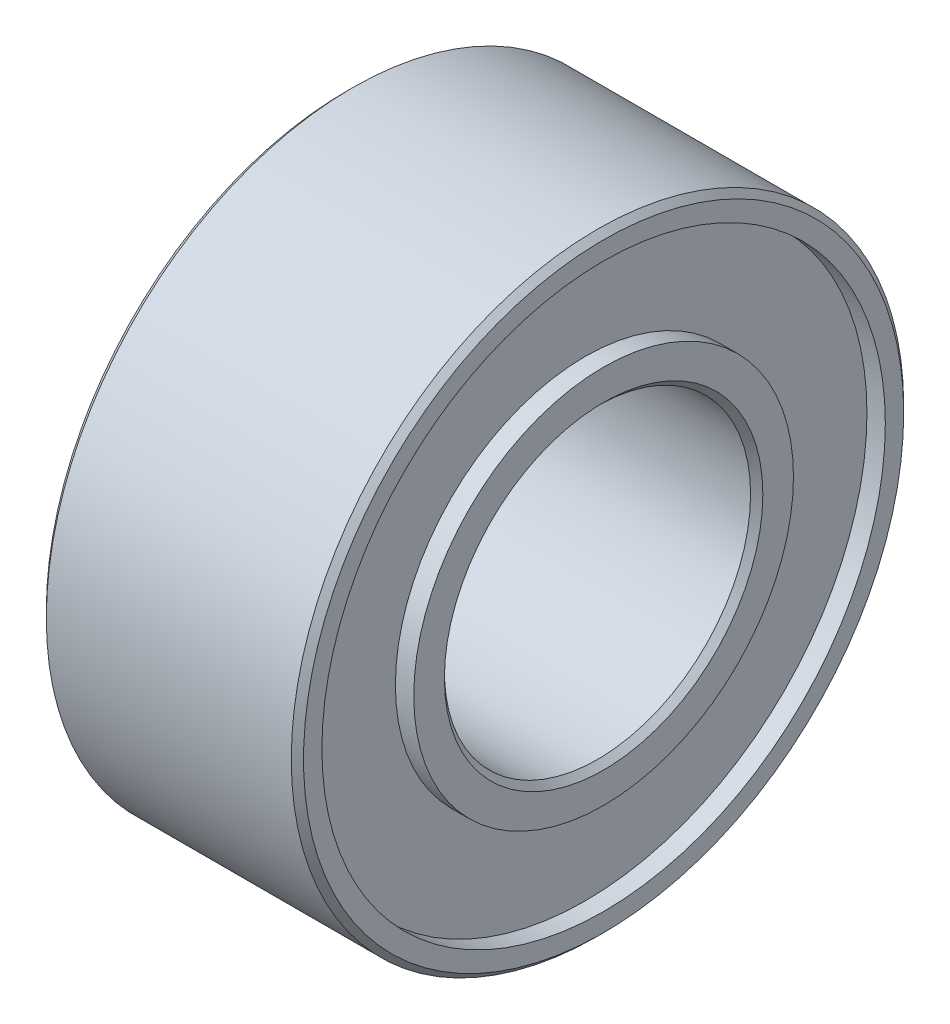
SolidWorks part; units mm, degrees
material "Plain Carbon Steel"
ref_plane "Front Plane" through (0, 0, 0) normal (0, 0, 1) x (1, 0, 0)
ref_plane "Top Plane" through (0, 0, 0) normal (0, 1, 0) x (1, 0, 0)
ref_plane "Right Plane" through (0, 0, 0) normal (1, 0, 0) x (0, 0, -1)
sketch "Sketch1" plane through (0, 0, 0) normal (0, 0, 1) x (1, 0, 0)
  line L0 (2.1, 2.5) -> (-2.1, 2.5)
  line L1 (-2.1, 2.5) -> (-2.1, 3.1)
  line L2 (-2.1, 3.1) -> (-1.8, 3.1)
  line L3 (-1.8, 3.1) -> (-1.8, 4.6)
  line L4 (-1.8, 4.6) -> (-2.1, 4.6)
  line L5 (-2.1, 4.6) -> (-2.1, 5)
  line L6 (-2.1, 5) -> (2.1, 5)
  line L7 (0, 5) -> (0, 2.5) construction
  line L8 (2.1, 4.6) -> (2.1, 5)
  line L9 (1.8, 4.6) -> (2.1, 4.6)
  line L10 (1.8, 3.1) -> (1.8, 4.6)
  line L11 (2.1, 3.1) -> (1.8, 3.1)
  line L12 (2.1, 2.5) -> (2.1, 3.1)
  line L13 (0, 0) -> (-4.3663, 0) construction
  dimension "D1" = 5
  dimension "D2" = 10
  dimension "D3" = 4.2
  dimension "D4" = 6.2
  dimension "D5" = 1.5
  dimension "D6" = 0.3
revolve "Revolve1" add sketch "Sketch1" angle 360 about L13
chamfer "Chamfer1" distance 0.1 angle 45 4 edges at (-2.1, 0, -2.5) (2.1, 0, -2.5) (-2.1, 0, -5) (2.1, 0, -5)
